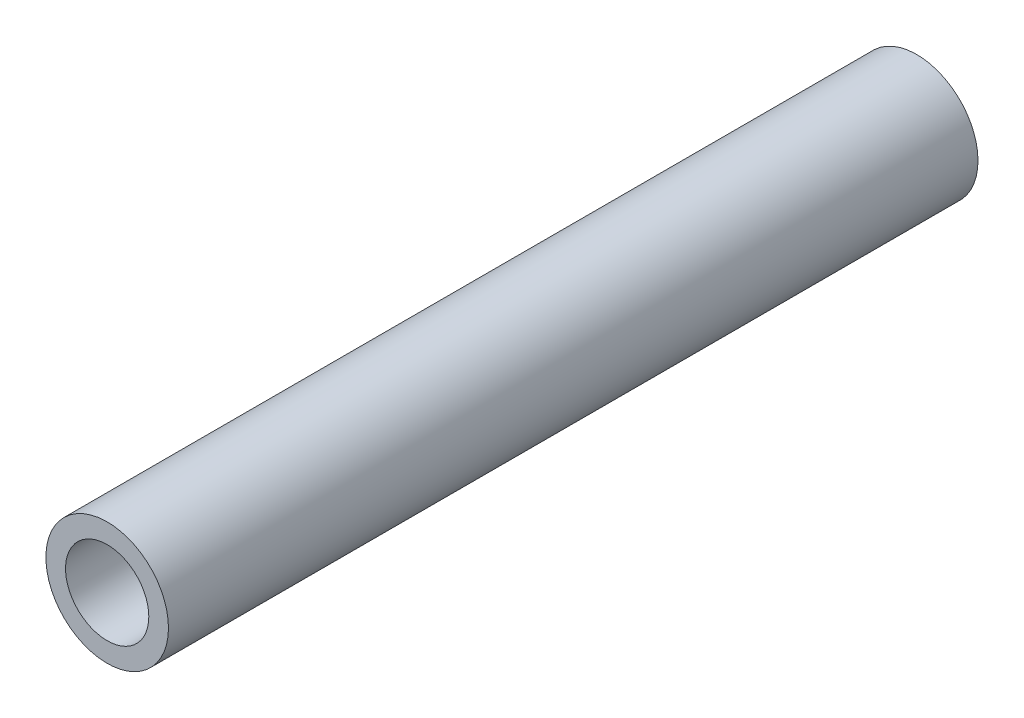
SolidWorks part; units mm, degrees
ref_plane "Front Plane" through (0, 0, 0) normal (0, 0, 1) x (1, 0, 0)
ref_plane "Top Plane" through (0, 0, 0) normal (0, 1, 0) x (1, 0, 0)
ref_plane "Right Plane" through (0, 0, 0) normal (1, 0, 0) x (0, 0, -1)
sketch "Sketch1" plane through (0, 0, 0) normal (0, 0, 1) x (1, 0, 0)
  circle A0 centre (0, 0) radius 2.65
  circle A1 centre (0, 0) radius 1.8
  dimension "D1" = 5.3
  dimension "D2" = 3.6
extrude "Boss-Extrude1" add sketch "Sketch1" along normal blind 35
